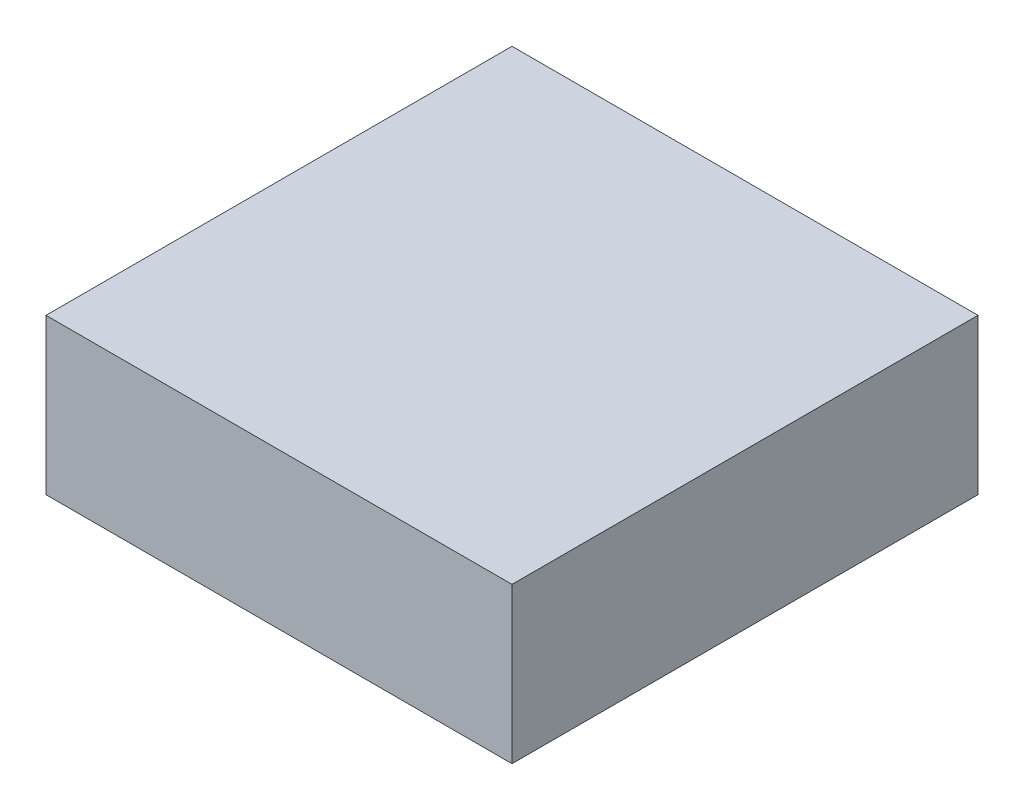
SolidWorks part; units mm, degrees
ref_plane "前视基准面" through (0, 0, 0) normal (0, 0, 1) x (1, 0, 0)
ref_plane "上视基准面" through (0, 0, 0) normal (0, 1, 0) x (1, 0, 0)
ref_plane "右视基准面" through (0, 0, 0) normal (1, 0, 0) x (0, 0, -1)
sketch "草图1" plane through (0, 0, 0) normal (0, 1, 0) x (1, 0, 0)
  line L4 (-3.3333, 80) -> (-3.3333, -10)
  line L5 (-3.3333, -10) -> (86.6667, -10)
  line L6 (86.6667, 80) -> (86.6667, -10)
  line L7 (-3.3333, 80) -> (86.6667, 80)
  dimension "D1" = 90
  dimension "D2" = 90
extrude "凸台-拉伸1" add sketch "草图1" along normal blind 30
